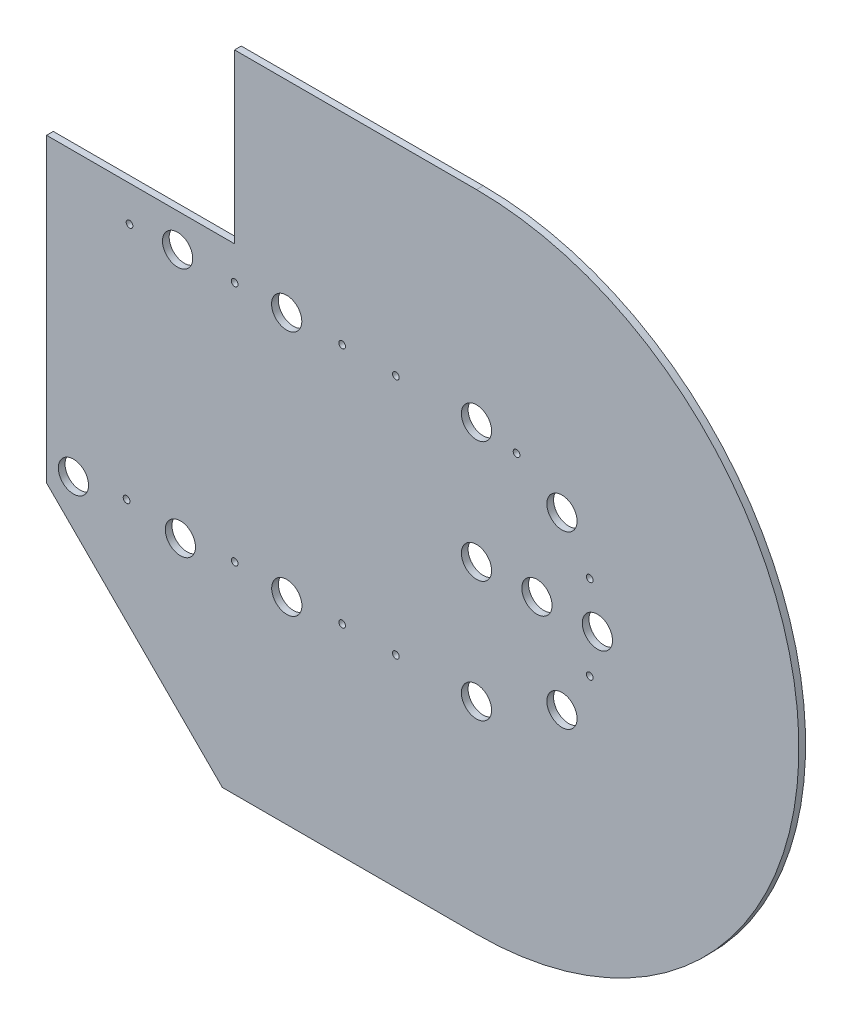
SolidWorks part; units mm, degrees
ref_plane "Front Plane" through (0, 0, 0) normal (0, 0, 1) x (1, 0, 0)
ref_plane "Top Plane" through (0, 0, 0) normal (0, 1, 0) x (1, 0, 0)
ref_plane "Right Plane" through (0, 0, 0) normal (1, 0, 0) x (0, 0, -1)
sketch "Model" plane through (0, 0, 0) normal (0, 0, 1) x (1, 0, 0)
  line L0 (0, 304.8) -> (-406.4, 304.8)
  line L1 (-222.25, -304.8) -> (0, -304.8)
  line L2 (-406.4, -120.65) -> (-406.4, 304.8)
  line L3 (-406.4, -120.65) -> (-406.4, -138.6105)
  line L4 (-406.4, -138.6105) -> (-240.2105, -304.8)
  line L5 (-240.2105, -304.8) -> (-222.25, -304.8)
  circle A0 centre (-282.5572, 114.3) radius 14.2875
  circle A1 centre (-179.4086, 114.3) radius 14.2875
  circle A2 centre (0, 114.3) radius 14.2875
  circle A3 centre (80.8223, 80.8223) radius 14.2875
  circle A4 centre (114.3, 0) radius 14.2875
  circle A5 centre (80.8223, -80.8223) radius 14.2875
  circle A6 centre (0, -114.3) radius 14.2875
  circle A7 centre (-179.3163, -118.368) radius 14.2875
  circle A8 centre (-381, -120.65) radius 14.2875
  circle A9 centre (-279.9047, -120.65) radius 14.2875
  circle A10 centre (0, 0) radius 14.2875
  circle A11 centre (57.15, 0) radius 14.2875
  circle A12 centre (37.8936, 107.8358) radius 3.175
  circle A13 centre (107.0902, 39.9522) radius 3.175
  circle A14 centre (107.0902, -39.9522) radius 3.175
  arc A15 (0, -304.8) -> (0, 304.8) centre (0, 0) ccw
  circle A16 centre (-327.9816, 112.5318) radius 3.175
  circle A17 centre (-330.7857, -114.2893) radius 3.175
  circle A18 centre (-228.6, 114.3) radius 3.175
  circle A19 centre (-127, 114.3) radius 3.175
  circle A20 centre (-76.2, 114.3) radius 3.175
  circle A21 centre (-76.2, -114.3) radius 3.175
  circle A22 centre (-127, -114.3) radius 3.175
  circle A23 centre (-228.6, -114.3) radius 3.175
extrude "Boss-Extrude1" add sketch "Model" along normal blind 6.35
sketch "Sketch2" plane through (0, 0, 6.35) normal (0, 0, 1) x (1, 0, 0)
  line L0 (-406.4, 304.8) -> (-406.4, -138.6105) construction
  line L1 (-406.4, 304.8) -> (-228.7178, 304.8)
  line L2 (-406.4, 304.8) -> (-406.4, 146.05)
  line L3 (-406.4, 146.05) -> (-228.7178, 146.05)
  line L4 (-228.7178, 304.8) -> (-228.7178, 146.05)
  line L5 (0, 304.8) -> (-406.4, 304.8) construction
extrude "Cut-Extrude1" cut sketch "Sketch2" against normal blind 6.35
